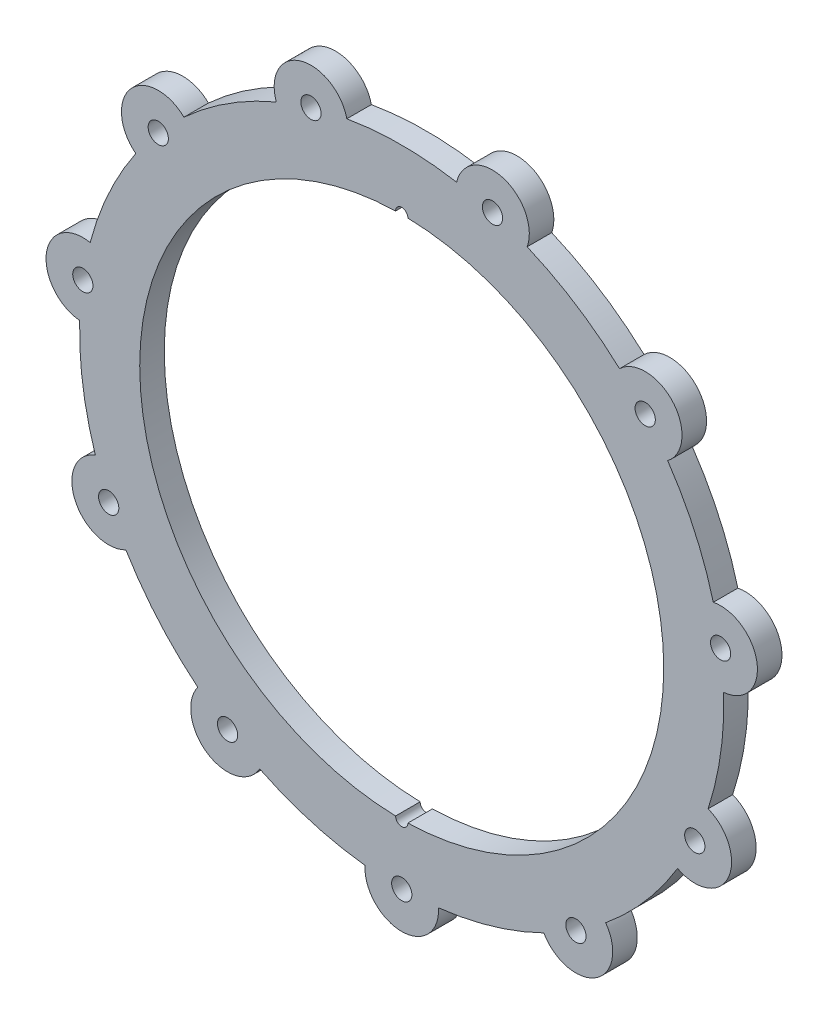
SolidWorks part; units mm, degrees
ref_plane "前视基准面" through (0, 0, 0) normal (0, 0, 1) x (1, 0, 0)
ref_plane "上视基准面" through (0, 0, 0) normal (0, 1, 0) x (1, 0, 0)
ref_plane "右视基准面" through (0, 0, 0) normal (1, 0, 0) x (0, 0, -1)
sketch "草图1" plane through (0, 0, 0) normal (0, 0, 1) x (1, 0, 0)
  line L0 (0, 0) -> (-51.9656, 7.4715) construction
  line L1 (-51.9656, 7.4715) -> (-73.6711, 10.5923) construction
  line L2 (0, 0) -> (-47.7557, -21.8093) construction
  line L3 (-47.7557, -21.8093) -> (-59.3488, -27.1037) construction
  circle A0 centre (0, 0) radius 42.7
  circle A1 centre (0, 0) radius 62.5 construction
  circle A2 centre (0, 0) radius 59 construction
  circle A19 centre (0, 0) radius 52.5 construction
  circle A23 centre (-51.9656, 7.4715) radius 1.65
  circle A103 centre (-47.7557, -21.8093) radius 6 construction
  circle A104 centre (-51.9656, 7.4715) radius 6 construction
  arc A105 (-57.9046, 8.3254) -> (-52.4788, 1.4935) centre (-51.9656, 7.4715) ccw
  arc A106 (-49.9322, -16.218) -> (-53.2135, -24.3018) centre (-47.7557, -21.8093) ccw
  arc A107 (-49.9322, -16.218) -> (-52.4788, 1.4935) centre (0, 0) cw
  arc A108 (-44.2114, 38.3094) -> (-43.3405, 29.6286) centre (-39.6769, 34.3802) ccw
  arc A109 (-50.7738, 13.352) -> (-43.3405, 29.6286) centre (0, 0) cw
  arc A110 (-50.7738, 13.352) -> (-57.9046, 8.3254) centre (-51.9656, 7.4715) ccw
  circle A111 centre (-39.6769, 34.3802) radius 1.65
  arc A112 (-16.4814, 56.1303) -> (-20.4419, 48.3568) centre (-14.791, 50.3734) ccw
  arc A113 (-35.495, 38.6828) -> (-20.4419, 48.3568) centre (0, 0) cw
  arc A114 (-35.495, 38.6828) -> (-44.2114, 38.3094) centre (-39.6769, 34.3802) ccw
  circle A115 centre (-14.791, 50.3734) radius 1.65
  arc A116 (16.4814, 56.1303) -> (8.9468, 51.732) centre (14.791, 50.3734) ccw
  arc A117 (-8.9468, 51.732) -> (8.9468, 51.732) centre (0, 0) cw
  arc A118 (-8.9468, 51.732) -> (-16.4814, 56.1303) centre (-14.791, 50.3734) ccw
  circle A119 centre (14.791, 50.3734) radius 1.65
  arc A120 (44.2114, 38.3094) -> (35.495, 38.6828) centre (39.6769, 34.3802) ccw
  arc A121 (20.4419, 48.3568) -> (35.495, 38.6828) centre (0, 0) cw
  arc A122 (20.4419, 48.3568) -> (16.4814, 56.1303) centre (14.791, 50.3734) ccw
  circle A123 centre (39.6769, 34.3802) radius 1.65
  arc A124 (57.9046, 8.3254) -> (50.7738, 13.352) centre (51.9656, 7.4715) ccw
  arc A125 (43.3405, 29.6286) -> (50.7738, 13.352) centre (0, 0) cw
  arc A126 (43.3405, 29.6286) -> (44.2114, 38.3094) centre (39.6769, 34.3802) ccw
  circle A131 centre (51.9656, 7.4715) radius 1.65
  arc A132 (53.2135, -24.3018) -> (49.9322, -16.218) centre (47.7557, -21.8093) ccw
  arc A133 (52.4788, 1.4935) -> (49.9322, -16.218) centre (0, 0) cw
  arc A134 (52.4788, 1.4935) -> (57.9046, 8.3254) centre (51.9656, 7.4715) ccw
  circle A135 centre (47.7557, -21.8093) radius 1.65
  arc A136 (31.6275, -49.2133) -> (33.2376, -40.6388) centre (28.3836, -44.1658) ccw
  arc A137 (44.9554, -27.1157) -> (33.2376, -40.6388) centre (0, 0) cw
  circle A191 centre (-47.7557, -21.8093) radius 1.65 construction
  circle A209 centre (14.791, 50.3734) radius 1.65 [skipped]
  circle A214 centre (39.6769, 34.3802) radius 1.65 [skipped]
  circle A220 centre (51.9656, 7.4715) radius 1.65 [skipped]
  circle A226 centre (47.7557, -21.8093) radius 1.65 [skipped]
  circle A232 centre (28.3836, -44.1658) radius 1.65 [skipped]
  circle A238 centre (0, -52.5) radius 1.65 [skipped]
  arc A243 (44.9554, -27.1157) -> (53.2135, -24.3018) centre (47.7557, -21.8093) ccw
  circle A244 centre (28.3836, -44.1658) radius 1.65
  arc A245 (0, -58.5) -> (5.9902, -52.1571) centre (0, -52.5) ccw
  arc A246 (23.159, -47.1159) -> (5.9902, -52.1571) centre (0, 0) cw
  arc A247 (23.159, -47.1159) -> (31.6275, -49.2133) centre (28.3836, -44.1658) ccw
  circle A248 centre (0, -52.5) radius 1.65
  arc A249 (-31.6275, -49.2133) -> (-23.159, -47.1159) centre (-28.3836, -44.1658) ccw
  circle A252 centre (-28.3836, -44.1658) radius 1.65 [skipped]
  arc A256 (-5.9902, -52.1571) -> (-23.159, -47.1159) centre (0, 0) cw
  circle A261 centre (-39.6769, 34.3802) radius 1.65 [skipped]
  circle A267 centre (-14.791, 50.3734) radius 1.65 [skipped]
  arc A269 (-5.9902, -52.1571) -> (0, -58.5) centre (0, -52.5) ccw
  circle A272 centre (-28.3836, -44.1658) radius 1.65
  arc A273 (-53.2135, -24.3018) -> (-44.9554, -27.1157) centre (-47.7557, -21.8093) ccw
  arc A274 (-33.2376, -40.6388) -> (-44.9554, -27.1157) centre (0, 0) cw
  arc A275 (-33.2376, -40.6388) -> (-31.6275, -49.2133) centre (-28.3836, -44.1658) ccw
  circle A276 centre (-47.7557, -21.8093) radius 1.65
  dimension "D1" = 85.4
  dimension "D3" = 118
  dimension "D6" = 105
  dimension "D5" = 11
extrude "凸台-拉伸1" add sketch "草图1" along normal blind 4
sketch "草图2" plane through (0, 0, 4) normal (0, 0, 1) x (1, 0, 0)
  circle A0 centre (0, -42.7) radius 1
  circle A1 centre (0, 0) radius 42.7 construction
  circle A2 centre (0, 42.7) radius 1
extrude "切除-拉伸1" cut sketch "草图2" against normal blind 4
equation "\"52.5×2\"=96.9638"
